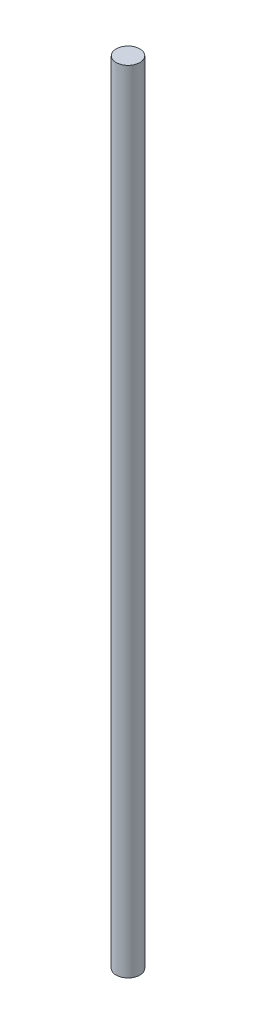
SolidWorks part; units mm, degrees
ref_plane "前视基准面" through (0, 0, 0) normal (0, 0, 1) x (1, 0, 0)
ref_plane "上视基准面" through (0, 0, 0) normal (0, 1, 0) x (1, 0, 0)
ref_plane "右视基准面" through (0, 0, 0) normal (1, 0, 0) x (0, 0, -1)
sketch "草图1" plane through (0, 0, 0) normal (0, 1, 0) x (1, 0, 0)
  circle A0 centre (0, 0) radius 3
  dimension "D1" = 6
extrude "凸台-拉伸1" add sketch "草图1" along normal blind 200
